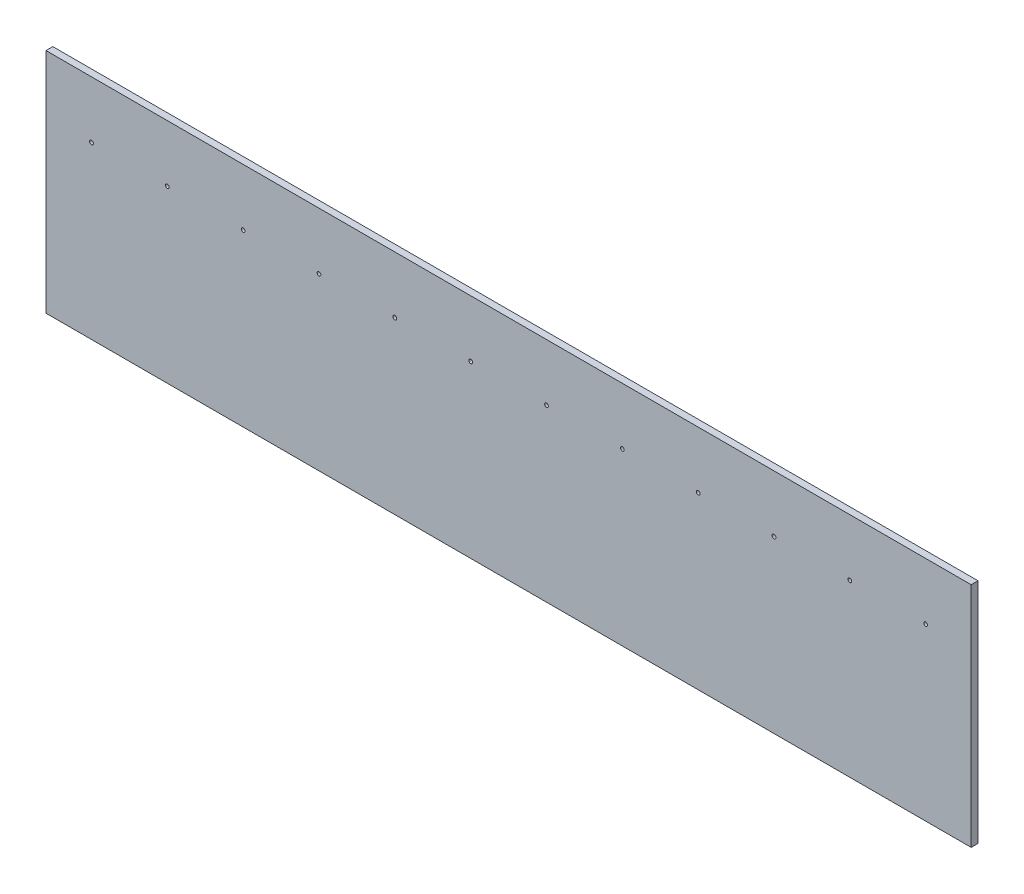
SolidWorks part; units mm, degrees
ref_plane "Front Plane" through (0, 0, 0) normal (0, 0, 1) x (1, 0, 0)
ref_plane "Top Plane" through (0, 0, 0) normal (0, 1, 0) x (1, 0, 0)
ref_plane "Right Plane" through (0, 0, 0) normal (1, 0, 0) x (0, 0, -1)
sketch "Sketch1" plane through (0, 0, 0) normal (0, 0, 1) x (1, 0, 0)
  line L1 (-789.7436, -341.0256) -> (1650.2564, -341.0256)
  line L2 (-789.7436, -341.0256) -> (-789.7436, 258.9744)
  line L3 (-789.7436, 258.9744) -> (1650.2564, 258.9744)
  line L4 (1650.2564, -341.0256) -> (1650.2564, 258.9744)
  circle A0 centre (-669.7436, 108.9744) radius 5
  circle A1 centre (-469.7436, 108.9744) radius 5
  circle A2 centre (-269.7436, 108.9744) radius 5
  circle A3 centre (-69.7436, 108.9744) radius 5
  circle A4 centre (130.2564, 108.9744) radius 5
  circle A5 centre (330.2564, 108.9744) radius 5
  circle A6 centre (530.2564, 108.9744) radius 5
  circle A7 centre (730.2564, 108.9744) radius 5
  circle A8 centre (930.2564, 108.9744) radius 5
  circle A9 centre (1130.2564, 108.9744) radius 5
  circle A10 centre (1330.2564, 108.9744) radius 5
  circle A11 centre (1530.2564, 108.9744) radius 5
  point P30 (-669.7436, 108.9744)
  point P31 (-469.7436, 108.9744)
  point P32 (-269.7436, 108.9744)
  point P33 (-69.7436, 108.9744)
  point P34 (130.2564, 108.9744)
  point P35 (330.2564, 108.9744)
  point P36 (530.2564, 108.9744)
  point P37 (730.2564, 108.9744)
  point P38 (930.2564, 108.9744)
  point P39 (1130.2564, 108.9744)
  point P40 (1330.2564, 108.9744)
  point P41 (1530.2564, 108.9744)
  dimension "D1" = 600
  dimension "D2" = 2440
extrude "Boss-Extrude1" add sketch "Sketch1" along normal blind 18
